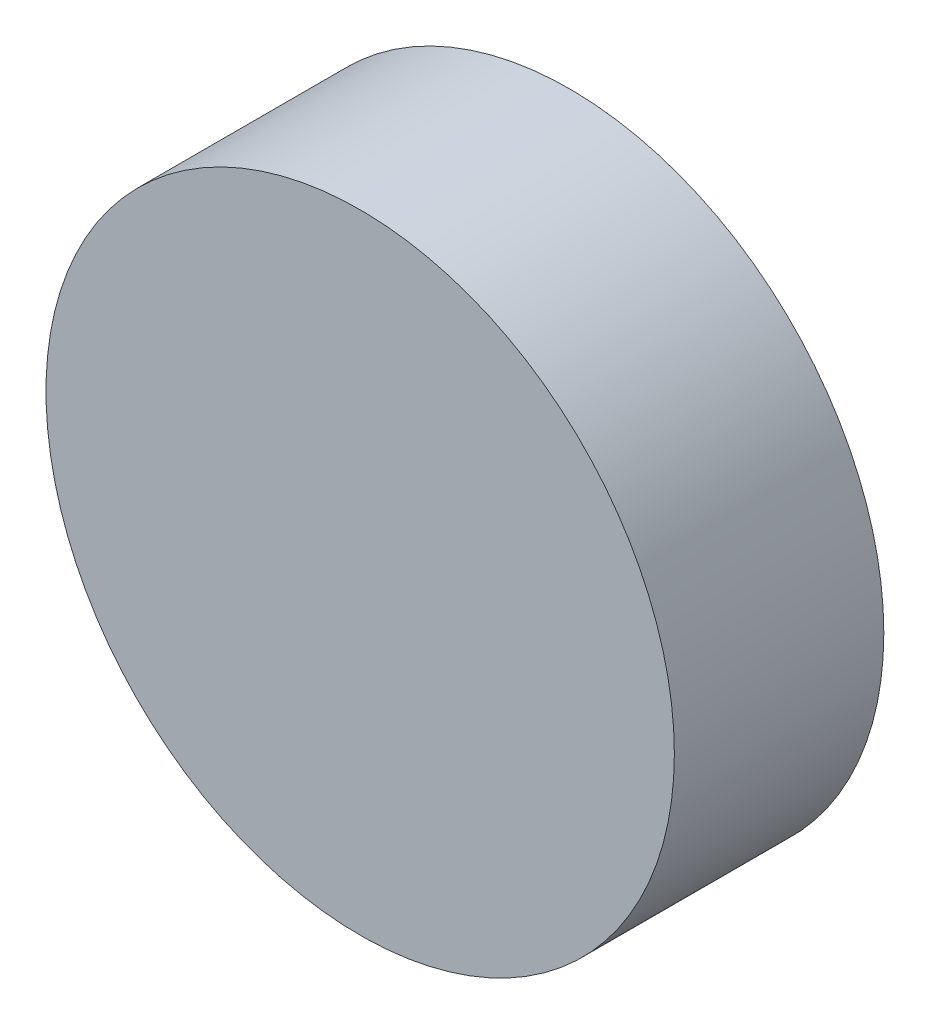
SolidWorks part; units mm, degrees
ref_plane "Front Plane" through (0, 0, 0) normal (0, 0, 1) x (1, 0, 0)
ref_plane "Top Plane" through (0, 0, 0) normal (0, 1, 0) x (1, 0, 0)
ref_plane "Right Plane" through (0, 0, 0) normal (1, 0, 0) x (0, 0, -1)
sketch "Sketch1" plane through (0, 0, 0) normal (0, 0, 1) x (1, 0, 0)
  circle A0 centre (0, 0) radius 5.25
  dimension "D1" = 10.5
extrude "Boss-Extrude1" add sketch "Sketch1" along normal blind 3.5
